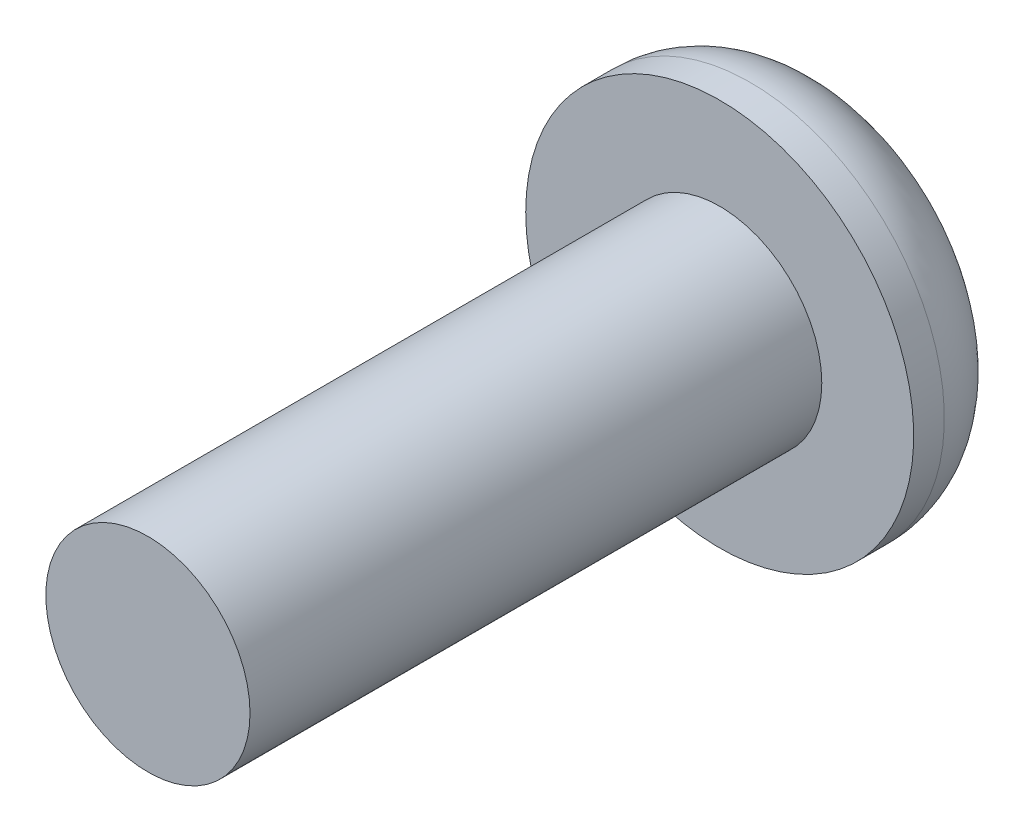
SolidWorks part; units mm, degrees
ref_plane "前视基准面" through (0, 0, 0) normal (0, 0, 1) x (1, 0, 0)
ref_plane "上视基准面" through (0, 0, 0) normal (0, 1, 0) x (1, 0, 0)
ref_plane "右视基准面" through (0, 0, 0) normal (1, 0, 0) x (0, 0, -1)
sketch "草图1" plane through (0, 0, 0) normal (0, 0, 1) x (1, 0, 0)
  circle A0 centre (0, 0) radius 2.5
extrude "凸台-拉伸1" add sketch "草图1" along normal blind 14
sketch "草图2" plane through (0, 0, 0) normal (0, 0, -1) x (-1, 0, 0)
  circle A0 centre (0, 0) radius 4.75
extrude "凸台-拉伸2" add sketch "草图2" along normal blind 2.75
fillet "圆角1" radius 2 1 edges at (-4.75, 0, -2.75)
